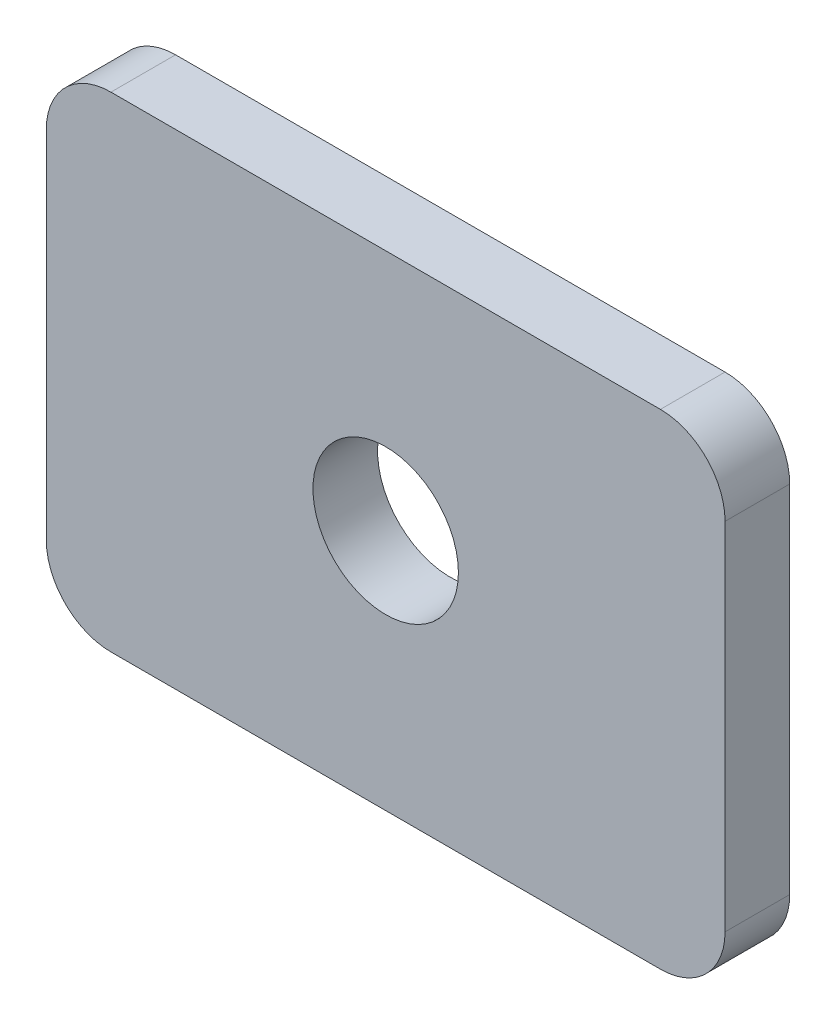
SolidWorks part; units mm, degrees
material "ABS"
ref_plane "Front Plane" through (0, 0, 0) normal (0, 0, 1) x (1, 0, 0)
ref_plane "Top Plane" through (0, 0, 0) normal (0, 1, 0) x (1, 0, 0)
ref_plane "Right Plane" through (0, 0, 0) normal (1, 0, 0) x (0, 0, -1)
sketch "Sketch1" plane through (0, 0, 0) normal (0, 0, 1) x (1, 0, 0)
  line L1 (-10.5, 7.5) -> (10.5, 7.5)
  line L2 (-10.5, 7.5) -> (-10.5, -7.5)
  line L3 (-10.5, -7.5) -> (10.5, -7.5)
  line L4 (10.5, 7.5) -> (10.5, -7.5)
  line L5 (-10.5, 7.5) -> (10.5, -7.5) construction
  line L6 (-10.5, -7.5) -> (10.5, 7.5) construction
  point P0 (0, 0)
  dimension "D1" = 21
  dimension "D2" = 15
extrude "Boss-Extrude1" add sketch "Sketch1" against normal blind 2
sketch "Sketch2" plane through (0, 0, 0) normal (0, 0, 1) x (1, 0, 0)
  circle A0 centre (0, 0) radius 2.25
  dimension "D1" = 4.5
extrude "Cut-Extrude1" cut sketch "Sketch2" against normal through all
fillet "Fillet1" radius 2 4 edges at (10.5, 7.5, -1) (10.5, -7.5, -1) (-10.5, -7.5, -1) (-10.5, 7.5, -1)
